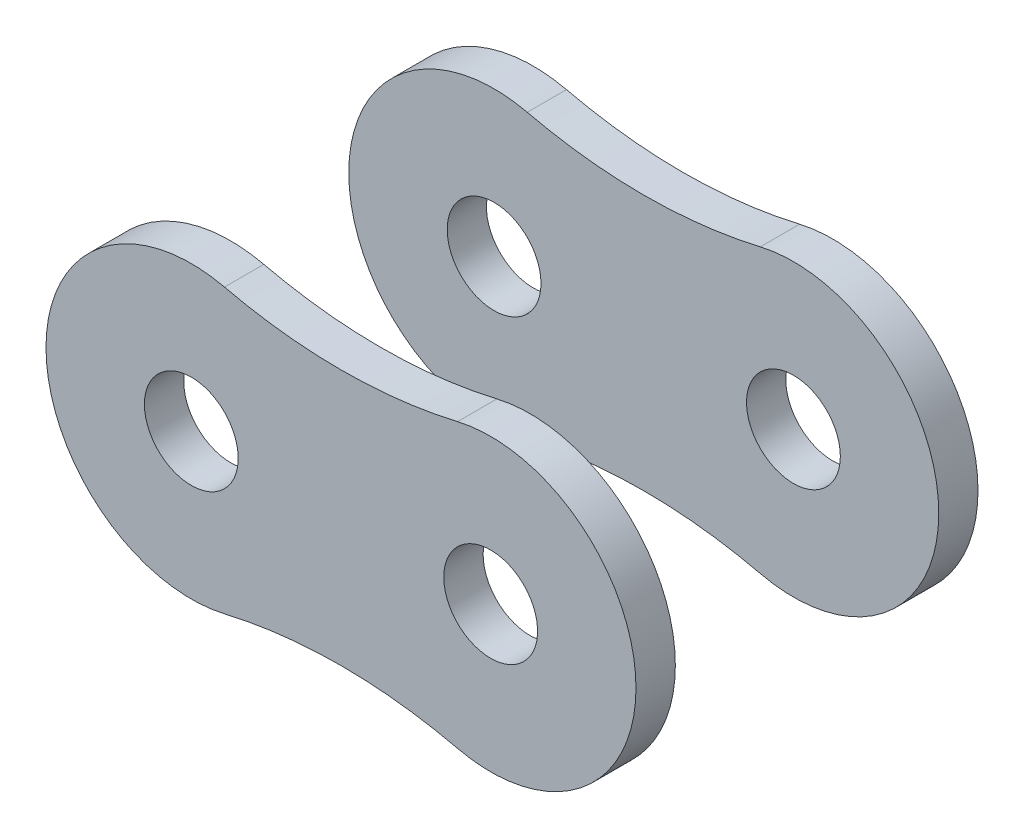
SolidWorks part; units mm, degrees
ref_plane "前视基准面" through (0, 0, 0) normal (0, 0, 1) x (1, 0, 0)
ref_plane "上视基准面" through (0, 0, 0) normal (0, 1, 0) x (1, 0, 0)
ref_plane "右视基准面" through (0, 0, 0) normal (1, 0, 0) x (0, 0, -1)
sketch "草图1" plane through (0, 0, 0) normal (0, 0, 1) x (1, 0, 0)
  line L0 (-6.35, 0) -> (6.35, 0) construction
  line L1 (0, 5.4315) -> (0, -5.4315) construction
  line L2 (6.35, 0) -> (14.2, 0) construction
  line L3 (14.2, 0) -> (25.38, 0) construction
  circle A4 centre (-6.35, 0) radius 6.165
  circle A5 centre (6.35, 0) radius 6.165
  circle A6 centre (0, 27.1196) radius 21.6881
  circle A7 centre (0, -27.1196) radius 21.6881
  circle A8 centre (-6.35, 0) radius 1.99
  circle A9 centre (6.35, 0) radius 1.99
  dimension "h1" = 12.33
  dimension "d2" = 3.98
  dimension "p" = 12.7
  dimension "h3" = 10.863
  dimension "b1" = 7.85
  dimension "b2" = 11.18
sketch "草图2" plane through (0, 0, 0) normal (0, 0, 1) x (1, 0, 0)
  circle A0 centre (-6.35, 0) radius 6.165 construction
  arc A1 (-4.9445, 6.0026) -> (-4.9445, -6.0026) centre (-6.35, 0) ccw
  circle A2 centre (6.35, 0) radius 6.165 construction
  arc A3 (4.9445, -6.0026) -> (4.9445, 6.0026) centre (6.35, 0) ccw
  circle A4 centre (0, 27.1196) radius 21.6881 construction
  arc A5 (-4.9445, 6.0026) -> (4.9445, 6.0026) centre (0, 27.1196) ccw
  circle A6 centre (0, -27.1196) radius 21.6881 construction
  arc A7 (4.9445, -6.0026) -> (-4.9445, -6.0026) centre (0, -27.1196) ccw
extrude "拉伸1" add sketch "草图2" along normal blind 1.665
sketch "草图3" plane through (0, 0, 1.665) normal (0, 0, 1) x (1, 0, 0)
  circle A0 centre (-6.35, 0) radius 1.99 construction
  circle A1 centre (-6.35, 0) radius 1.99
  circle A2 centre (6.35, 0) radius 1.99 construction
  circle A3 centre (6.35, 0) radius 1.99
extrude "切除-拉伸1" cut sketch "草图3" against normal through all
ref_plane "基准面1" through (0, 0, 14.51) normal (0, 0, -1) x (-1, 0, 0)
sketch "草图4" plane through (0, 0, 14.51) normal (0, 0, -1) x (-1, 0, 0)
  arc A0 (4.9445, -6.0026) -> (4.9445, 6.0026) centre (6.35, 0) ccw construction
  circle A1 centre (6.35, 0) radius 1.99 construction
  circle A2 centre (-6.35, 0) radius 1.99 construction
  arc A3 (-4.9445, 6.0026) -> (-4.9445, -6.0026) centre (-6.35, 0) ccw construction
  arc A4 (-4.9445, 6.0026) -> (4.9445, 6.0026) centre (0, 27.1196) ccw construction
  arc A5 (4.9445, -6.0026) -> (4.9445, 6.0026) centre (6.35, 0) ccw
  circle A6 centre (6.35, 0) radius 1.99
  circle A7 centre (-6.35, 0) radius 1.99
  arc A8 (-4.9445, 6.0026) -> (-4.9445, -6.0026) centre (-6.35, 0) ccw
  arc A9 (-4.9445, 6.0026) -> (4.9445, 6.0026) centre (0, 27.1196) ccw
  arc A10 (4.9445, -6.0026) -> (-4.9445, -6.0026) centre (0, -27.1196) ccw construction
  arc A11 (4.9445, -6.0026) -> (-4.9445, -6.0026) centre (0, -27.1196) ccw
extrude "凸台-拉伸1" add sketch "草图4" along normal blind 1.67 separate body
ref_plane "基准面2" through (0, 0, 7.255) normal (0, 0, -1) x (-1, 0, 0)
sketch "草图5" plane through (0, 0, 7.255) normal (0, 0, -1) x (-1, 0, 0)
  point P0 (6.35, 0)
  point P1 (-6.35, 0)
equation "\"D@拉伸1\" = (  \"b2@草图1\" - \"b1@草图1\" )  / 2"
